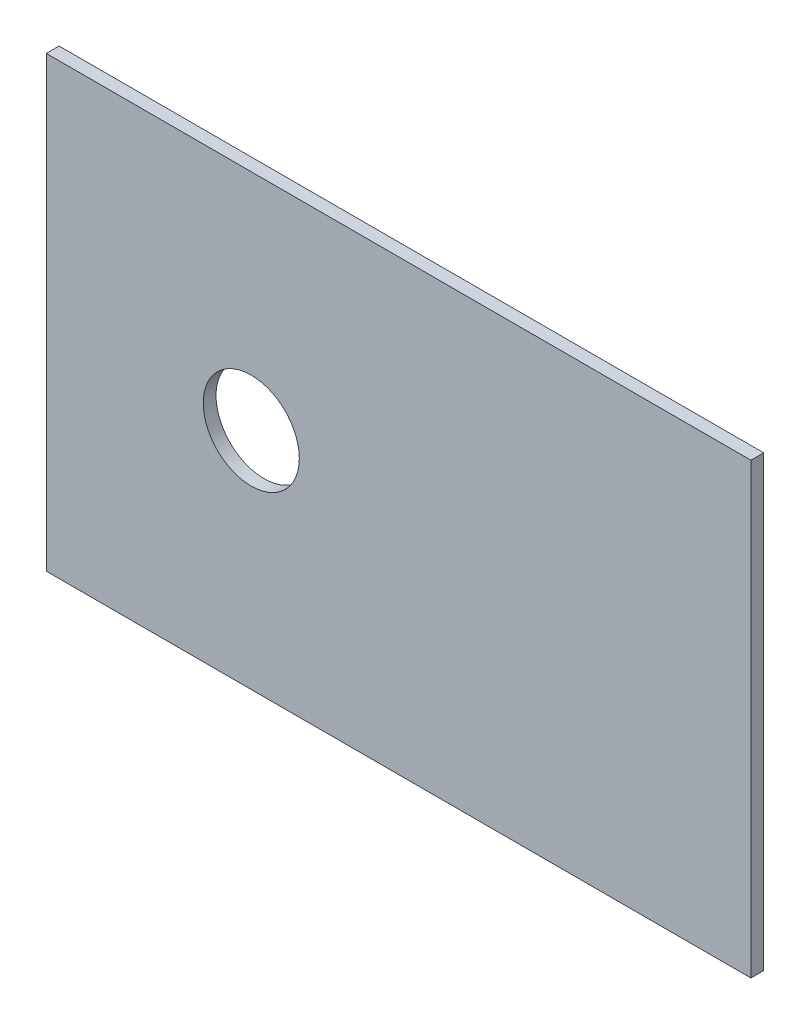
SolidWorks part; units mm, degrees
ref_plane "Front Plane" through (0, 0, 0) normal (0, 0, 1) x (1, 0, 0)
ref_plane "Top Plane" through (0, 0, 0) normal (0, 1, 0) x (1, 0, 0)
ref_plane "Right Plane" through (0, 0, 0) normal (1, 0, 0) x (0, 0, -1)
sketch "Sketch1" plane through (0, 0, 0) normal (0, 0, 1) x (1, 0, 0)
  line L1 (-60.3966, 25.8655) -> (79.3034, 25.8655)
  line L2 (-60.3966, 25.8655) -> (-60.3966, -63.0345)
  line L3 (-60.3966, -63.0345) -> (79.3034, -63.0345)
  line L4 (79.3034, 25.8655) -> (79.3034, -63.0345)
  dimension "D1" = 139.7
  dimension "D2" = 88.9
extrude "Boss-Extrude1" add sketch "Sketch1" along normal blind 2.54
sketch "Sketch2" plane through (0, 0, 2.54) normal (0, 0, 1) x (1, 0, 0)
  line L0 (-60.3966, 25.8655) -> (-60.3966, -63.0345) construction
  circle A0 centre (-19.7566, -18.5845) radius 9.525
  point P4 (-19.7566, -18.1527)
  dimension "D2" = 19.05
  dimension "D1" = 40.64
  dimension "D3" = 44.45
extrude "Cut-Extrude1" cut sketch "Sketch2" against normal blind 2.54
